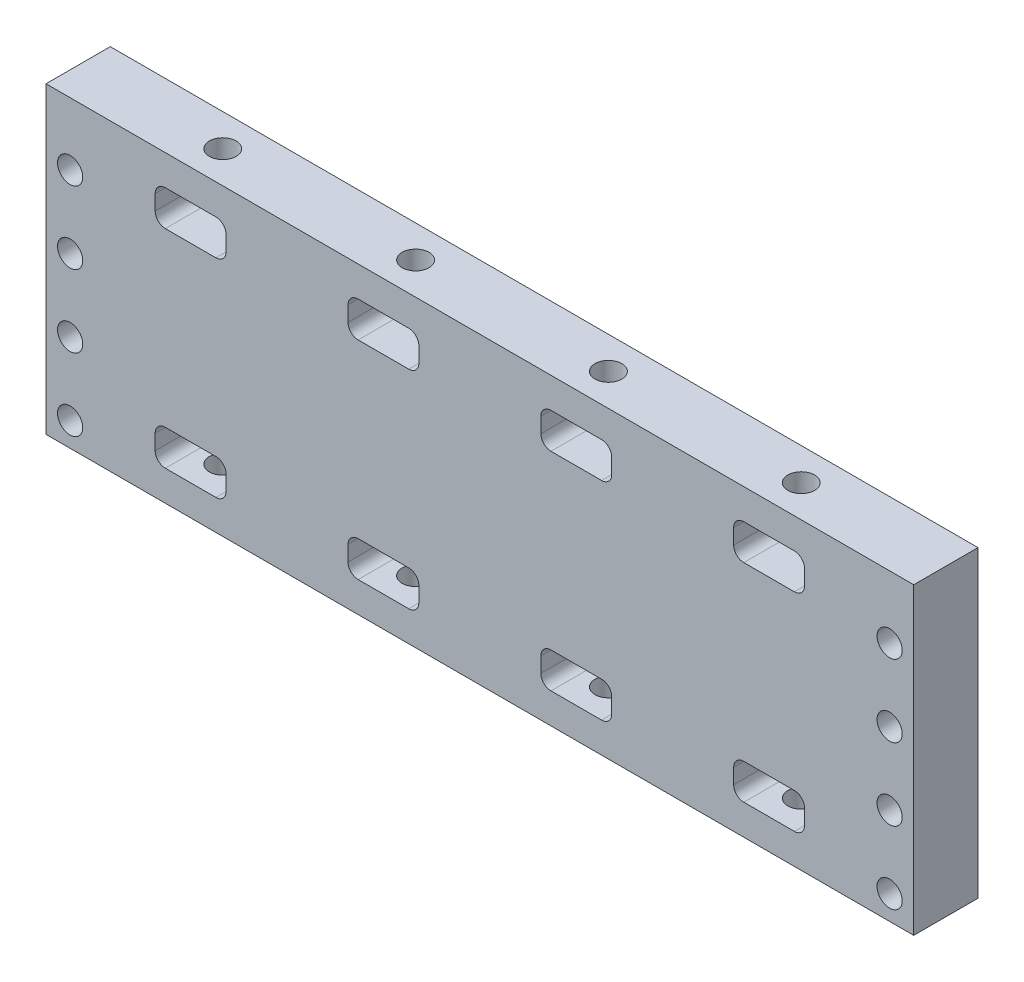
SolidWorks part; units mm, degrees
material "6061-T6 (SS)"
ref_plane "Front Plane" through (0, 0, 0) normal (0, 0, 1) x (1, 0, 0)
ref_plane "Top Plane" through (0, 0, 0) normal (0, 1, 0) x (1, 0, 0)
ref_plane "Right Plane" through (0, 0, 0) normal (1, 0, 0) x (0, 0, -1)
sketch "Sketch1" plane through (0, 0, 0) normal (0, 0, 1) x (1, 0, 0)
  line L1 (-85.725, -30) -> (85.725, -30)
  line L2 (-85.725, -30) -> (-85.725, 30)
  line L3 (-85.725, 30) -> (85.725, 30)
  line L4 (85.725, -30) -> (85.725, 30)
  line L5 (-85.725, -30) -> (85.725, 30) construction
  line L6 (-85.725, 30) -> (85.725, -30) construction
  point P0 (0, 0)
  dimension "D1" = 171.45
  dimension "D2" = 60
extrude "Boss-Extrude1" add sketch "Sketch1" along normal mid plane 12.7
sketch "Sketch2" [suppressed] plane through (0, 0, 6.35) normal (0, 0, 1) x (1, 0, 0)
  line L0 (85.725, 30) -> (-85.725, 30) construction
  line L1 (0, 0) -> (85.725, 0) construction
  line L2 (85.725, -30) -> (85.725, 30) construction
  point P0 (0, 22)
  point P8 (0, -22)
  dimension "D1" = 8
hole_wizard "M5 Clearance Hole1" [suppressed] positions "Sketch3" profile "Sketch4" hole size "M5" standard "ANSI Metric"
sketch "Sketch3" plane through (0, 0, 6.35) normal (0, 0, 1) x (1, 0, 0)
  point P0 (0, 22)
  point P3 (0, -22)
sketch "Sketch4" plane through (0, 22, 6.35) normal (1, 0, 0) x (0, -1, 0)
  line L0 (0, 0) -> (0, 12.7)
  line L1 (0, 12.7) -> (2.65, 12.7)
  line L2 (2.65, 12.7) -> (2.65, 0)
  line L5 (2.65, 0) -> (0, 0)
  line L11 (0, -6.35) -> (0, 107.95) construction
  dimension "Thru Hole Dia." = 5.3
  dimension "Thru Hole Depth" = 12.7
sketch "Sketch6" plane through (0, 0, 6.35) normal (0, 0, 1) x (1, 0, 0)
  circle A0 centre (0, 0) radius 6.35
  point P0 (0, 0)
  dimension "D1" = 12.7
extrude "Cut-Extrude1" [suppressed] cut sketch "Sketch6" against normal through all
sketch "Sketch7" [suppressed] plane through (0, 0, -6.35) normal (0, 0, -1) x (-1, 0, 0)
  line L5 (-66.675, 0) -> (66.675, 0) construction
  line L6 (-66.675, 6.35) -> (66.675, 6.35)
  line L8 (-66.675, -6.35) -> (66.675, -6.35)
  line L9 (-85.725, -30) -> (-85.725, 30) construction
  arc A1 (-66.675, 6.35) -> (-66.675, -6.35) centre (-66.675, 0) ccw
  arc A2 (66.675, -6.35) -> (66.675, 6.35) centre (66.675, 0) ccw
  circle A3 centre (0, 0) radius 6.35 construction
  point P0 (0, 0)
  point P3 (0, 0)
  point P12 (-73.025, 0)
  dimension "D1" = 12.7
extrude "Cut-Extrude2" [suppressed] cut sketch "Sketch7" against normal blind 4
sketch "Sketch8" [suppressed] plane through (0, 0, -6.35) normal (0, 0, -1) x (-1, 0, 0)
  line L0 (-67.925, 11.35) -> (-65.425, 11.35) construction
  line L1 (-67.925, 12.35) -> (-65.425, 12.35)
  line L2 (-67.925, 10.35) -> (-65.425, 10.35)
  line L3 (-85.725, -30) -> (-85.725, 30) construction
  line L4 (0, 6.35) -> (-66.675, 6.35) construction
  line L6 (-48.875, 10.35) -> (-46.375, 10.35)
  line L7 (-48.875, 12.35) -> (-46.375, 12.35)
  line L8 (-48.875, 11.35) -> (-46.375, 11.35) construction
  line L9 (-29.825, 10.35) -> (-27.325, 10.35)
  line L10 (-29.825, 12.35) -> (-27.325, 12.35)
  line L11 (-29.825, 11.35) -> (-27.325, 11.35) construction
  line L12 (-10.775, 10.35) -> (-8.275, 10.35)
  line L13 (-10.775, 12.35) -> (-8.275, 12.35)
  line L14 (-10.775, 11.35) -> (-8.275, 11.35) construction
  line L15 (8.275, 10.35) -> (10.775, 10.35)
  line L16 (8.275, 12.35) -> (10.775, 12.35)
  line L17 (8.275, 11.35) -> (10.775, 11.35) construction
  line L18 (27.325, 10.35) -> (29.825, 10.35)
  line L19 (27.325, 12.35) -> (29.825, 12.35)
  line L20 (27.325, 11.35) -> (29.825, 11.35) construction
  line L21 (46.375, 10.35) -> (48.875, 10.35)
  line L22 (46.375, 12.35) -> (48.875, 12.35)
  line L23 (46.375, 11.35) -> (48.875, 11.35) construction
  line L24 (65.425, 10.35) -> (67.925, 10.35)
  line L25 (65.425, 12.35) -> (67.925, 12.35)
  line L26 (65.425, 11.35) -> (67.925, 11.35) construction
  arc A0 (-67.925, 12.35) -> (-67.925, 10.35) centre (-67.925, 11.35) ccw
  arc A1 (-65.425, 10.35) -> (-65.425, 12.35) centre (-65.425, 11.35) ccw
  arc A2 (-48.875, 12.35) -> (-48.875, 10.35) centre (-48.875, 11.35) ccw
  arc A3 (-46.375, 10.35) -> (-46.375, 12.35) centre (-46.375, 11.35) ccw
  arc A4 (-29.825, 12.35) -> (-29.825, 10.35) centre (-29.825, 11.35) ccw
  arc A5 (-27.325, 10.35) -> (-27.325, 12.35) centre (-27.325, 11.35) ccw
  arc A6 (-10.775, 12.35) -> (-10.775, 10.35) centre (-10.775, 11.35) ccw
  arc A7 (-8.275, 10.35) -> (-8.275, 12.35) centre (-8.275, 11.35) ccw
  arc A8 (8.275, 12.35) -> (8.275, 10.35) centre (8.275, 11.35) ccw
  arc A9 (10.775, 10.35) -> (10.775, 12.35) centre (10.775, 11.35) ccw
  arc A10 (27.325, 12.35) -> (27.325, 10.35) centre (27.325, 11.35) ccw
  arc A11 (29.825, 10.35) -> (29.825, 12.35) centre (29.825, 11.35) ccw
  arc A12 (46.375, 12.35) -> (46.375, 10.35) centre (46.375, 11.35) ccw
  arc A13 (48.875, 10.35) -> (48.875, 12.35) centre (48.875, 11.35) ccw
  arc A14 (65.425, 12.35) -> (65.425, 10.35) centre (65.425, 11.35) ccw
  arc A15 (67.925, 10.35) -> (67.925, 12.35) centre (67.925, 11.35) ccw
  point P2 (-66.675, 11.35)
  point P15 (-47.625, 11.35)
  point P22 (-28.575, 11.35)
  point P29 (-9.525, 11.35)
  point P36 (9.525, 11.35)
  point P43 (28.575, 11.35)
  point P50 (47.625, 11.35)
  point P57 (66.675, 11.35)
  dimension "D1" = 2.5
  dimension "D2" = 2
  dimension "D3" = 19.05
  dimension "D6" = 19.05
  dimension "D4" = 5
  dimension "D5" = 8
extrude "Cut-Extrude3" [suppressed] cut sketch "Sketch8" against normal through all
mirror "Mirror1" [suppressed] about plane through (0, 0, 0) normal (0, 1, 0)
sketch "Sketch9" plane through (0, 0, 6.35) normal (0, 0, 1) x (1, 0, 0)
  line L0 (-85.725, -30) -> (85.725, -30) construction
  line L1 (-85.725, 30) -> (-76.2, 30) construction
  line L2 (-85.725, 30) -> (-85.725, -30) construction
  line L3 (-85.725, -30) -> (-76.2, -30) construction
  line L4 (-76.2, 30) -> (-76.2, -30) construction
  line L5 (0, 0) -> (0, 30) construction
  line L6 (85.725, 30) -> (-85.725, 30) construction
  line L7 (-80.9625, 30) -> (-80.9625, -30) construction
  line L8 (85.725, 30) -> (76.2, 30) construction
  line L9 (85.725, 30) -> (85.725, -30) construction
  line L10 (85.725, -30) -> (76.2, -30) construction
  line L11 (76.2, 30) -> (76.2, -30) construction
  line L12 (80.9625, 30) -> (80.9625, -30) construction
  line L13 (80.9625, -25.2375) -> (80.9625, -10.95) construction
  point P21 (-80.9625, -25.2375)
  point P22 (80.9625, -25.2375)
  point P25 (-80.9625, -10.95)
  point P26 (80.9625, -10.95)
  point P27 (-80.9625, 3.3375)
  point P28 (80.9625, 3.3375)
  point P29 (-80.9625, 17.625)
  point P30 (80.9625, 17.625)
  dimension "D1" = 9.525
  dimension "D2" = 9.525
  dimension "D3" = 4.7625
  dimension "D5" = 14.2875
  dimension "D4" = 4
hole_wizard "#10 Clearance Hole1" positions "Sketch10" profile "Sketch11" hole size "#10" standard "ANSI Inch" end condition up to next
sketch "Sketch10" plane through (0, 0, 6.35) normal (0, 0, 1) x (1, 0, 0)
  point P0 (-80.9625, 17.625)
  point P3 (-80.9625, 3.3375)
  point P6 (-80.9625, -10.95)
  point P9 (-80.9625, -25.2375)
  point P12 (80.9625, 17.625)
  point P15 (80.9625, 3.3375)
  point P18 (80.9625, -10.95)
  point P21 (80.9625, -25.2375)
sketch "Sketch11" plane through (-80.9625, 17.625, 6.35) normal (1, 0, 0) x (0, -1, 0)
  line L0 (0, 0) -> (0, 12.7)
  line L1 (0, 12.7) -> (2.4892, 12.7)
  line L2 (2.4892, 12.7) -> (2.4892, 0)
  line L5 (2.4892, 0) -> (0, 0)
  line L11 (0, -6.35) -> (0, 107.95) construction
  dimension "Thru Hole Dia." = 4.9784
  dimension "Thru Hole Depth" = 12.7
sketch "Sketch12" plane through (0, 0, 6.35) normal (0, 0, 1) x (1, 0, 0)
  line L1 (-64.15, 24) -> (-50.15, 24)
  line L2 (-64.15, 24) -> (-64.15, 17)
  line L3 (-64.15, 17) -> (-50.15, 17)
  line L4 (-50.15, 24) -> (-50.15, 17)
  line L5 (-64.15, 24) -> (-50.15, 17) construction
  line L6 (-64.15, 17) -> (-50.15, 24) construction
  line L7 (85.725, 30) -> (-85.725, 30) construction
  line L8 (-85.725, 30) -> (-85.725, -30) construction
  point P0 (-57.15, 20.5)
  dimension "D1" = 14
  dimension "D2" = 7
  dimension "D3" = 6
  dimension "D4" = 28.575
extrude "Cut-Extrude4" cut sketch "Sketch12" against normal through all
fillet "Fillet2" radius 2 4 edges at (-50.15, 17, 0) (-64.15, 17, 0) (-50.15, 24, 0) (-64.15, 24, 0)
sketch "Sketch13" plane through (0, 0, 6.35) normal (0, 0, 1) x (1, 0, 0)
  line L0 (85.725, 30) -> (-85.725, 30) construction
  line L1 (-85.725, 30) -> (-85.725, -30) construction
  line L2 (-57.15, 20.5) -> (-19.05, 20.5) construction
  line L3 (-85.725, 0) -> (85.725, 0) construction
  line L4 (85.725, -30) -> (85.725, 30) construction
  point P0 (-57.15, 20.5)
  point P7 (-19.05, 20.5)
  point P8 (19.05, 20.5)
  point P9 (57.15, 20.5)
  point P16 (57.15, -20.5)
  point P17 (19.05, -20.5)
  point P18 (-57.15, -20.5)
  point P19 (-19.05, -20.5)
  dimension "D4" = 4
  dimension "D1" = 9.5
  dimension "D2" = 28.575
  dimension "D3" = 38.1
pattern_sketch "Sketch-Pattern1" of "Cut-Extrude4", "Fillet2" driven by "Sketch13"
sketch "Sketch14" plane through (0, 30, 0) normal (0, 1, 0) x (1, 0, 0)
  line L0 (-85.725, -6.35) -> (-85.725, 6.35) construction
  line L1 (-57.15, 0) -> (-19.05, 0) construction
  point P0 (-57.15, 0)
  point P3 (-19.05, 0)
  point P5 (19.05, 0)
  point P7 (57.15, 0)
  dimension "D1" = 28.575
  dimension "D2" = 38.1
hole_wizard "M5 Clearance Hole2" positions "Sketch15" profile "Sketch16" hole size "M5" standard "ANSI Metric"
sketch "Sketch15" plane through (0, 30, 0) normal (0, 1, 0) x (1, 0, 0)
  point P0 (-57.15, 0)
  point P3 (-19.05, 0)
  point P6 (19.05, 0)
  point P9 (57.15, 0)
sketch "Sketch16" plane through (-57.15, 30, 0) normal (1, 0, 0) x (0, 0, 1)
  line L0 (0, 0) -> (0, 6)
  line L1 (0, 6) -> (2.65, 6)
  line L2 (2.65, 6) -> (2.65, 0)
  line L5 (2.65, 0) -> (0, 0)
  line L11 (0, -6.35) -> (0, 107.95) construction
  dimension "Thru Hole Dia." = 5.3
  dimension "Thru Hole Depth" = 6
hole_wizard "M5 Clearance Hole3" positions "Sketch17" profile "Sketch18" hole size "M5" standard "ANSI Metric"
sketch "Sketch17" plane through (0, -30, 0) normal (0, -1, 0) x (-1, 0, 0)
  point P0 (-57.15, 0)
  point P3 (-19.05, 0)
  point P6 (19.05, 0)
  point P9 (57.15, 0)
sketch "Sketch18" plane through (57.15, -30, 0) normal (1, 0, 0) x (0, 0, -1)
  line L0 (0, 0) -> (0, 6)
  line L1 (0, 6) -> (2.65, 6)
  line L2 (2.65, 6) -> (2.65, 0)
  line L5 (2.65, 0) -> (0, 0)
  line L11 (0, -6.35) -> (0, 107.95) construction
  dimension "Thru Hole Dia." = 5.3
  dimension "Thru Hole Depth" = 6
equation "\"D1@Sketch1\"=6.75in"
equation "\"D1@Boss-Extrude1\"=0.5in"
equation "\"D1@Sketch6\"=0.5in"
equation "\"D1@Sketch7\"=0.5in"
equation "\"D1@Sketch9\"=0.375in"
equation "\"D2@Sketch9\"=0.375in"
equation "\"D3@Sketch9\"=0.1875in"
equation "\"D3@Sketch8\"=0.75in"
equation "\"D4@Sketch12\"=0.75in + 0.75in/2"
equation "\"D2@Sketch13\"=0.75in + 0.75in/2"
equation "\"D1@Sketch14\"=0.75in + 0.75in/2"
